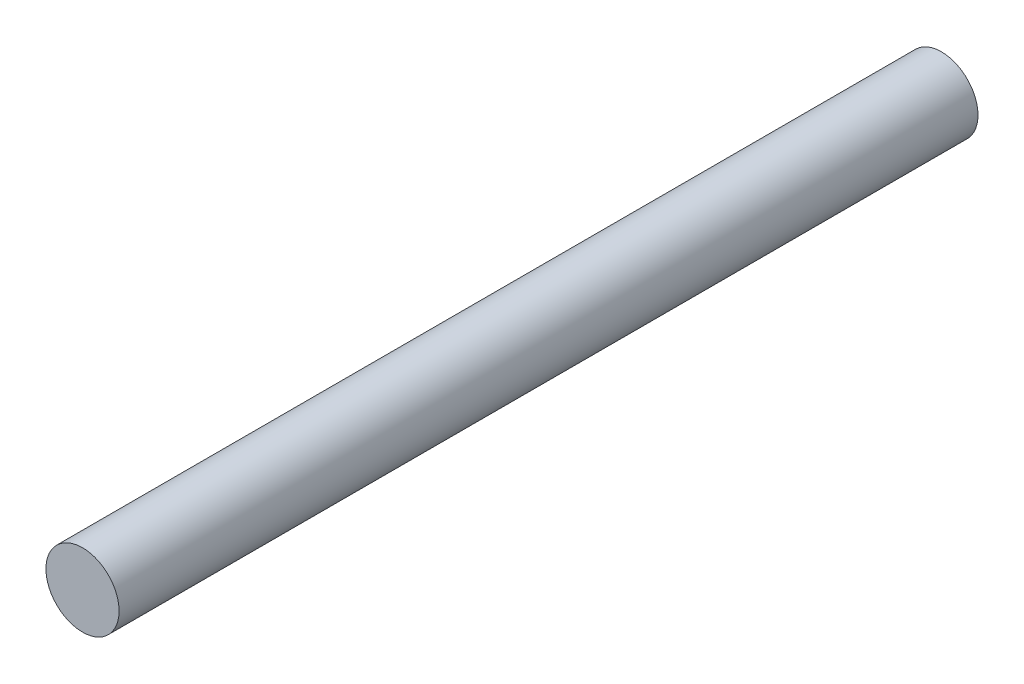
SolidWorks part; units mm, degrees
material "AISI 316 Annealed Stainless Steel Bar (SS)"
ref_plane "Front Plane" through (0, 0, 0) normal (0, 0, 1) x (1, 0, 0)
ref_plane "Top Plane" through (0, 0, 0) normal (0, 1, 0) x (1, 0, 0)
ref_plane "Right Plane" through (0, 0, 0) normal (1, 0, 0) x (0, 0, -1)
sketch "Sketch1" plane through (0, 0, 0) normal (0, 0, 1) x (1, 0, 0)
  circle A0 centre (0, 0) radius 1.8923
  dimension "D1" = 3.7846
extrude "Boss-Extrude1" add sketch "Sketch1" along normal blind 44.45
